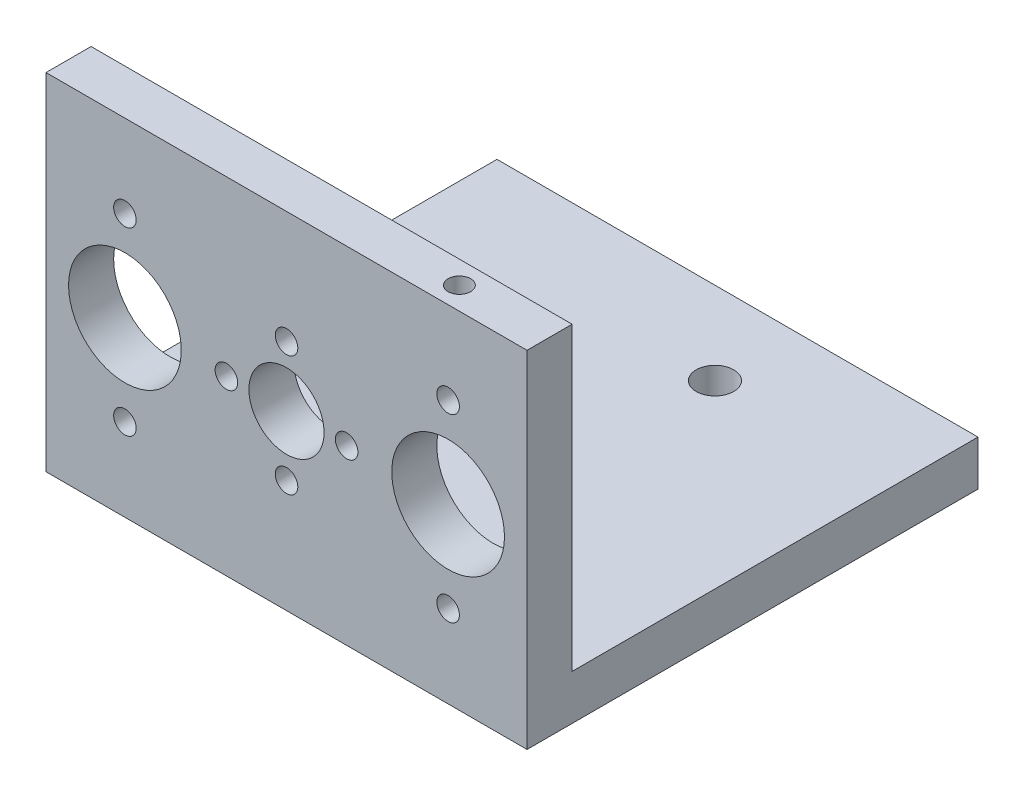
SolidWorks part; units mm, degrees
ref_plane "前视基准面" through (0, 0, 0) normal (0, 0, 1) x (1, 0, 0)
ref_plane "上视基准面" through (0, 0, 0) normal (0, 1, 0) x (1, 0, 0)
ref_plane "右视基准面" through (0, 0, 0) normal (1, 0, 0) x (0, 0, -1)
sketch "草图1" plane through (0, 0, 0) normal (1, 0, 0) x (0, 0, -1)
  line L0 (6, 6) -> (0, 6) construction
  line L1 (0, 0) -> (80, 0)
  line L2 (0, 0) -> (0, 6)
  line L3 (6, 6) -> (80, 6)
  line L4 (80, 0) -> (80, 6)
  line L6 (0, 6) -> (0, 80)
  line L7 (0, 80) -> (6, 80)
  line L8 (6, 6) -> (6, 80)
  dimension "D1" = 6
  dimension "D2" = 80
  dimension "D3" = 6
  dimension "D4" = 74
extrude "凸台-拉伸1" add sketch "草图1" along normal blind 104
sketch "草图2" plane through (0, 6, 0) normal (0, 1, 0) x (1, 0, 0)
  line L0 (104, 6) -> (0, 6) construction
  line L1 (60, 11) -> (60, 49) construction
  line L2 (104, 80) -> (0, 80) construction
  line L3 (84, 60) -> (20, 60)
  line L5 (84, 80) -> (0, 80)
  line L6 (0, 80) -> (0, 6)
  line L7 (84, 6) -> (84, 60)
  line L8 (84, 6) -> (104, 6)
  line L9 (104, 6) -> (104, 80)
  line L10 (104, 80) -> (84, 80)
  line L12 (20, 6) -> (0, 6)
  line L13 (20, 6) -> (20, 60)
  circle A12 centre (60, 11) radius 2.5
  circle A13 centre (60, 49) radius 2.5
  dimension "D1" = 38
  dimension "D4" = 5
  dimension "D2" = 11
  dimension "D3" = 40
extrude "切除-拉伸1" cut sketch "草图2" against normal through all
sketch "草图3" plane through (0, 0, -6) normal (0, 0, -1) x (-1, 0, 0)
  line L0 (-84, 6) -> (-20, 6) construction
  line L1 (-52, 6) -> (-52, 80) construction
  line L2 (-104, 80) -> (0, 80) construction
  line L3 (-52, 23) -> (-24.9179, 23) construction
  line L4 (-84, 0) -> (-84, 46)
  line L6 (-104, 80) -> (-104, 0)
  line L7 (-104, 0) -> (-84, 0)
  line L8 (-84, 46) -> (-20, 46)
  line L9 (-104, 80) -> (0, 80)
  line L10 (-84, 6) -> (-20, 6) construction
  line L11 (-20, 0) -> (-20, 46)
  line L12 (0, 0) -> (-20, 0)
  line L13 (0, 80) -> (0, 0)
  circle A6 centre (-52, 23) radius 5
  circle A7 centre (-52, 15) radius 1.5
  circle A8 centre (-60, 23) radius 1.5
  circle A9 centre (-52, 31) radius 1.5
  circle A10 centre (-44, 23) radius 1.5
  circle A12 centre (-30.5, 23) radius 7.5
  circle A13 centre (-30.5, 35) radius 1.5
  circle A14 centre (-30.5, 11) radius 1.5
  circle A15 centre (-73.5, 11) radius 1.5
  circle A16 centre (-73.5, 23) radius 7.5
  circle A17 centre (-73.5, 35) radius 1.5
  point P29 (-52, 46)
  point P33 (-52, 23)
  dimension "D1" = 8
  dimension "D2" = 17
  dimension "D3" = 4
  dimension "D5" = 12
  dimension "D6" = 21.5
  dimension "D4" = 40
extrude "切除-拉伸2" cut sketch "草图3" against normal through all
sketch "草图4" plane through (0, 46, 0) normal (0, 1, 0) x (1, 0, 0)
  line L0 (84, 0) -> (84, 6) construction
  circle A0 centre (72, 3) radius 1.5
  dimension "D2" = 12
extrude "切除-拉伸3" cut sketch "草图4" against normal blind 5
